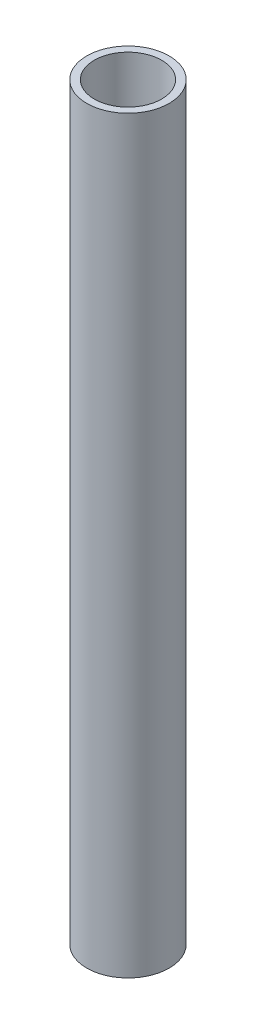
SolidWorks part; units mm, degrees
ref_plane "Front Plane" through (0, 0, 0) normal (0, 0, 1) x (1, 0, 0)
ref_plane "Top Plane" through (0, 0, 0) normal (0, 1, 0) x (1, 0, 0)
ref_plane "Right Plane" through (0, 0, 0) normal (1, 0, 0) x (0, 0, -1)
sketch "Sketch1" plane through (0, 0, 0) normal (0, 1, 0) x (1, 0, 0)
  circle A0 centre (0, 0) radius 5.5
  circle A1 centre (0, 0) radius 4.5
  dimension "D1" = 11
  dimension "D2" = 1
extrude "Boss-Extrude1" add sketch "Sketch1" along normal blind 100
